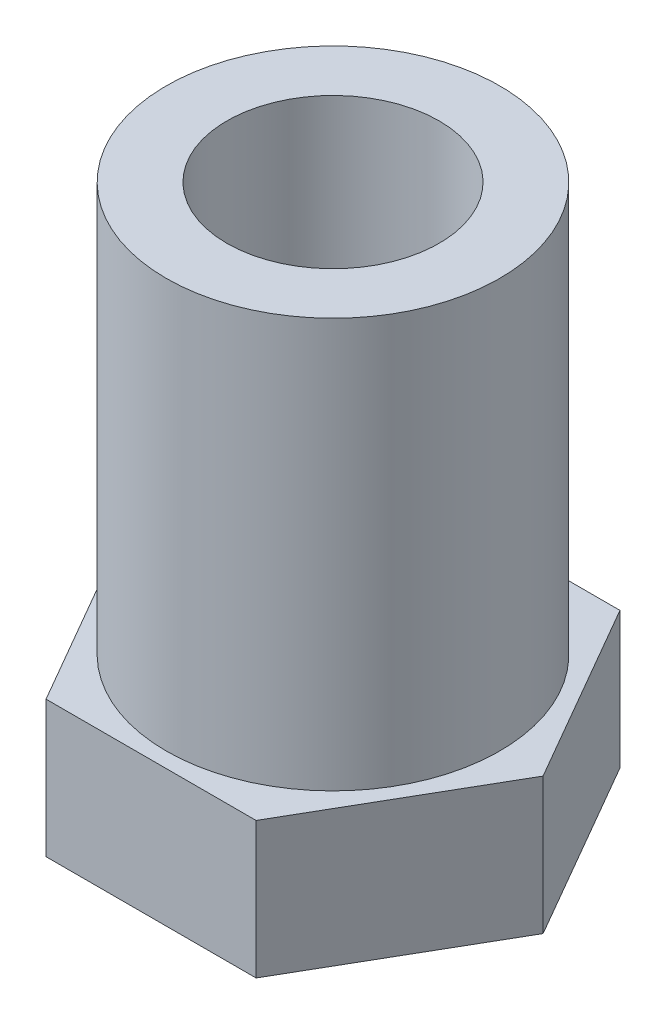
SolidWorks part; units mm, degrees
ref_plane "前视基准面" through (0, 0, 0) normal (0, 0, 1) x (1, 0, 0)
ref_plane "上视基准面" through (0, 0, 0) normal (0, 1, 0) x (1, 0, 0)
ref_plane "右视基准面" through (0, 0, 0) normal (1, 0, 0) x (0, 0, -1)
sketch "草图1" plane through (0, 0, 0) normal (0, 1, 0) x (1, 0, 0)
  line L1 (6.9282, 0) -> (3.4641, 6)
  line L2 (3.4641, 6) -> (-3.4641, 6)
  line L3 (-3.4641, 6) -> (-6.9282, 0)
  line L4 (-6.9282, 0) -> (-3.4641, -6)
  line L5 (-3.4641, -6) -> (3.4641, -6)
  line L6 (3.4641, -6) -> (6.9282, 0)
  circle A0 centre (0, 0) radius 6 construction
  circle A1 centre (0, 0) radius 2
  dimension "D1" = 12
extrude "凸台-拉伸1" add sketch "草图1" along normal blind 18
ref_plane "基准面1" through (0, 18, 0) normal (0, 1, 0) x (1, 0, 0)
sketch "草图2" plane through (0, 18, 0) normal (0, 1, 0) x (1, 0, 0)
  line L6 (3.4641, -6) -> (6.9282, 0)
  line L7 (6.9282, 0) -> (3.4641, 6)
  line L8 (3.4641, 6) -> (-3.4641, 6)
  line L9 (-3.4641, 6) -> (-6.9282, 0)
  line L10 (-6.9282, 0) -> (-3.4641, -6)
  line L11 (-3.4641, -6) -> (3.4641, -6)
  line L12 (3.4641, -6) -> (6.9282, 0)
  line L13 (6.9282, 0) -> (3.4641, 6)
  line L14 (3.4641, 6) -> (-3.4641, 6)
  line L15 (-3.4641, 6) -> (-6.9282, 0)
  line L16 (-6.9282, 0) -> (-3.4641, -6)
  line L17 (-3.4641, -6) -> (3.4641, -6)
  circle A0 centre (0, 0) radius 3.5
  circle A1 centre (0, 0) radius 5.5
  dimension "D1" = 7
  dimension "D2" = 11
  dimension "D3" = 0
extrude "切除-拉伸2" cut sketch "草图2" against normal blind 13.5 contours A0 | L16 L17 L12 L13 L14 L15 A1
